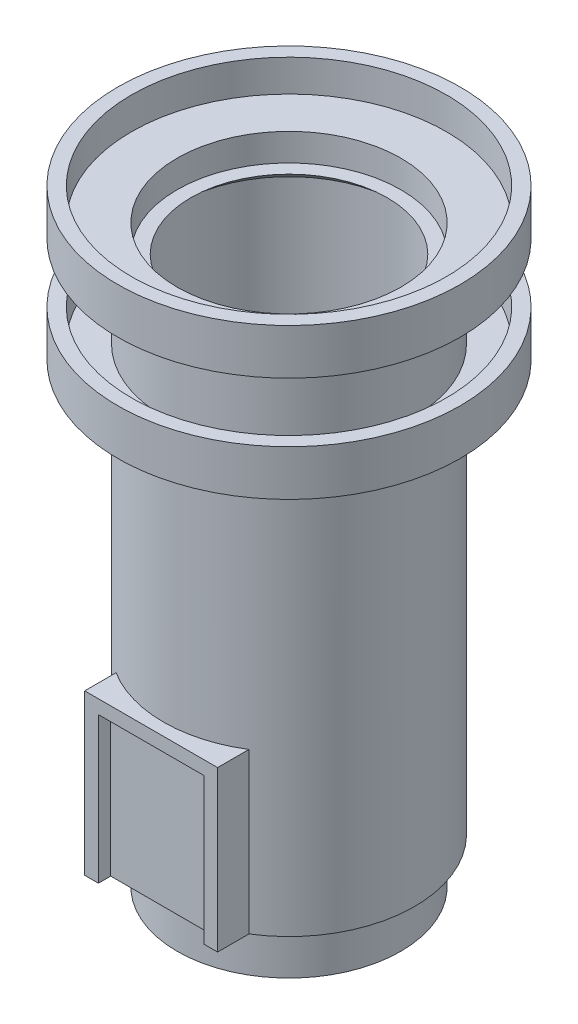
SolidWorks part; units mm, degrees
ref_plane "Alzado" through (0, 0, 0) normal (0, 0, 1) x (1, 0, 0)
ref_plane "Planta" through (0, 0, 0) normal (0, 1, 0) x (1, 0, 0)
ref_plane "Vista lateral" through (0, 0, 0) normal (1, 0, 0) x (0, 0, -1)
sketch "Croquis1" plane through (0, 0, 0) normal (0, 0, 1) x (1, 0, 0)
  line L0 (-17.713, 104.2623) -> (-17.713, 4.2623) construction
  line L1 (-39.213, 3.5199) -> (-39.213, 16.5199)
  line L2 (-39.213, 3.5199) -> (-42.213, 3.5199)
  line L3 (-42.213, 3.5199) -> (-42.213, 13.5199)
  line L4 (-42.213, 13.5199) -> (-45.213, 13.5199)
  line L5 (-45.213, 100.5199) -> (-45.213, 13.5199)
  line L6 (-39.213, 16.5199) -> (-42.213, 16.5199)
  line L8 (-45.213, 106.5199) -> (-45.213, 123.5199)
  line L9 (-55.213, 103.5199) -> (-55.213, 113.5199)
  line L10 (-55.213, 113.5199) -> (-52.213, 113.5199)
  line L11 (-52.213, 113.5199) -> (-52.213, 106.5199)
  line L12 (-52.213, 106.5199) -> (-45.213, 106.5199)
  line L13 (-45.213, 103.5199) -> (-45.213, 100.5199) construction
  line L14 (-55.213, 103.5199) -> (-45.213, 100.5199)
  line L17 (-55.213, 126.5199) -> (-45.213, 123.5199)
  line L18 (-55.213, 126.5199) -> (-55.213, 136.5199)
  line L19 (-55.213, 136.5199) -> (-52.213, 136.5199)
  line L20 (-52.213, 136.5199) -> (-52.213, 129.5199)
  line L21 (-52.213, 129.5199) -> (-42.213, 129.5199)
  line L22 (-45.213, 123.5199) -> (-39.213, 123.5199) construction
  line L23 (-42.213, 123.5199) -> (-39.213, 123.5199)
  line L24 (-42.213, 123.5199) -> (-42.213, 120.9176) construction
  line L25 (-39.213, 123.5199) -> (-42.213, 120.9176)
  line L26 (-42.213, 120.9176) -> (-42.213, 16.5199)
  line L27 (-42.213, 129.5199) -> (-42.213, 123.5199)
  dimension "D1" = 100
  dimension "D2" = 13
  dimension "D3" = 10
  dimension "D4" = 3
  dimension "D5" = 24.5
  dimension "D6" = 17
  dimension "D7" = 90
  dimension "D8" = 113
  dimension "D9" = 10
  dimension "D10" = 3
  dimension "D11" = 10
  dimension "D12" = 7
  dimension "D13" = 3
  dimension "D14" = 10
  dimension "D15" = 3
  dimension "D17" = 7
revolve "Revolución1" add sketch "Croquis1" angle 360 about L0
sketch "Croquis2" plane through (0, 13.5199, 0) normal (0, -1, 0) x (1, 0, 0)
  line L0 (-17.713, 27.5) -> (-17.713, 0) construction
  line L1 (-17.713, 23.3325) -> (-3.1582, 23.3325) construction
  line L3 (-32.2678, 23.3325) -> (-32.2678, 30.2025)
  line L4 (-3.1582, 23.3325) -> (-3.1582, 30.2025)
  line L5 (-32.2678, 30.2025) -> (-3.1582, 30.2025)
  circle A0 centre (-17.713, 0) radius 27.5 construction
  arc A1 (-32.2678, 23.3325) -> (-3.1582, 23.3325) centre (-17.713, 0) cw
  dimension "D1" = 6.87
  dimension "D2" = 6.87
extrude "Saliente-Extruir1" add sketch "Croquis2" against normal blind 35
sketch "Croquis3" plane through (0, 0, 30.2025) normal (0, 0, 1) x (1, 0, 0)
  line L0 (-3.1582, 13.5199) -> (-32.2678, 13.5199) construction
  line L1 (-29.2678, 13.5199) -> (-6.1582, 13.5199)
  line L2 (-29.2678, 13.5199) -> (-29.2678, 45.5199)
  line L3 (-29.2678, 45.5199) -> (-6.1582, 45.5199)
  line L4 (-6.1582, 13.5199) -> (-6.1582, 45.5199)
  line L5 (-3.1582, 48.5199) -> (-32.2678, 48.5199) construction
  line L6 (-32.2678, 48.5199) -> (-32.2678, 13.5199) construction
  line L7 (-3.1582, 48.5199) -> (-3.1582, 13.5199) construction
  dimension "D1" = 3
  dimension "D2" = 3
  dimension "D3" = 3
extrude "Cortar-Extruir1" cut sketch "Croquis3" against normal blind 2.7
